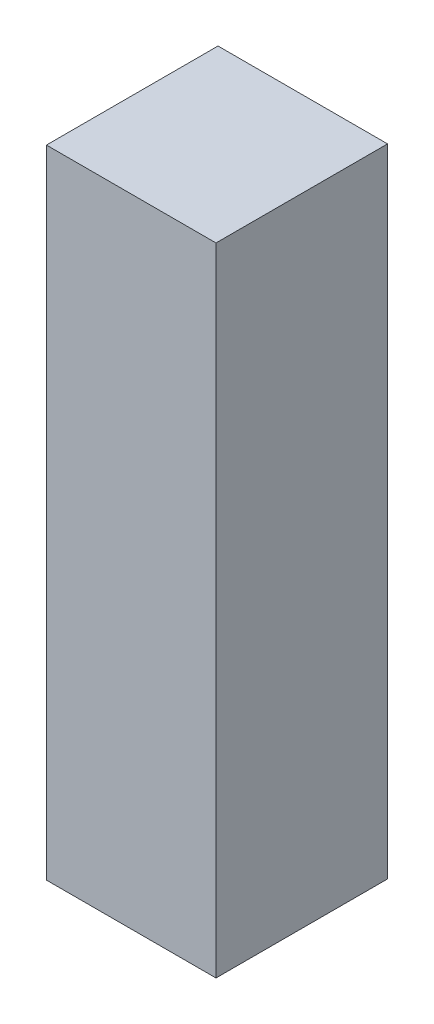
SolidWorks part; units mm, degrees
ref_plane "Front Plane" through (0, 0, 0) normal (0, 0, 1) x (1, 0, 0)
ref_plane "Top Plane" through (0, 0, 0) normal (0, 1, 0) x (1, 0, 0)
ref_plane "Right Plane" through (0, 0, 0) normal (1, 0, 0) x (0, 0, -1)
sketch "Sketch1" plane through (0, 0, 0) normal (1, 0, 0) x (0, 0, -1)
  line L1 (-18.9406, 43.5562) -> (-8.6602, 43.5562)
  line L2 (-18.9406, 43.5562) -> (-18.9406, 5.4107)
  line L3 (-18.9406, 5.4107) -> (-8.6602, 5.4107)
  line L4 (-8.6602, 43.5562) -> (-8.6602, 5.4107)
extrude "Boss-Extrude1" add sketch "Sketch1" along normal blind 10.16
